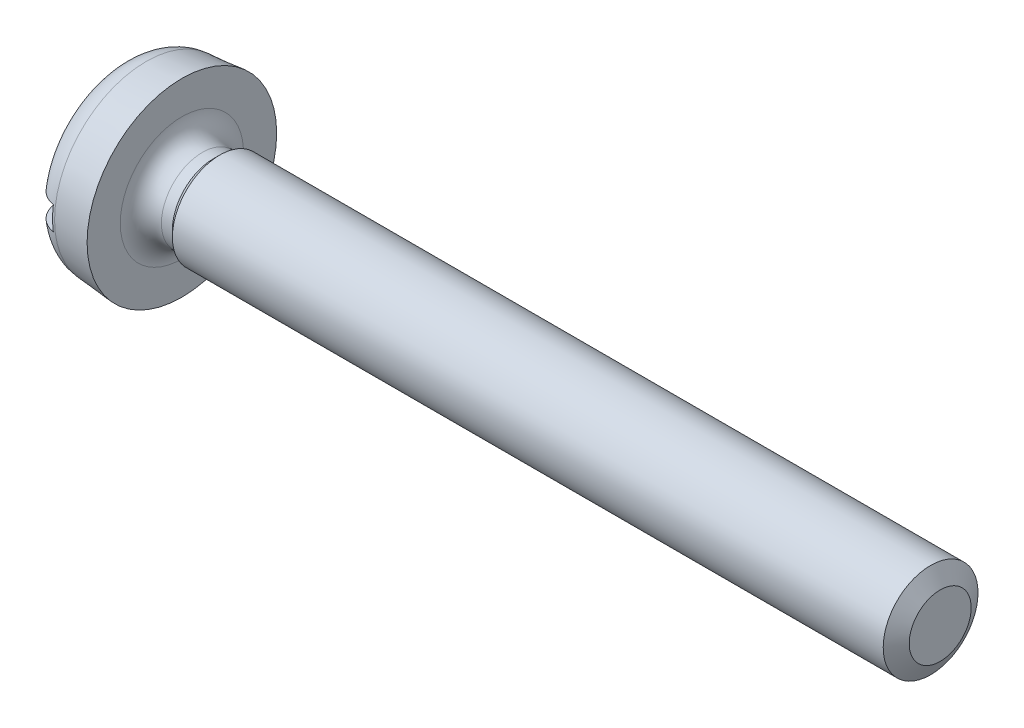
SolidWorks part; units mm, degrees
revolve "基体-旋转" add sketch "草图3" angle 360 about L0
sketch "草图3" plane through (0, 0, 0) normal (0, 0, 1) x (1, 0, 0)
  line L0 (-2.477, 0) -> (6.7868, 0) construction
  line L1 (0, 0) -> (17.3, 0)
  line L2 (17.3, 0) -> (17.3, 1)
  line L3 (17.3, 1) -> (2.1, 1)
  line L4 (1.3, 1.3) -> (1.3, 2)
  line L5 (2.1, 1) -> (1.966, 0.866)
  line L6 (1.966, 0.866) -> (1.734, 0.866)
  line L7 (1.3, 2) -> (0.5477, 1.9342)
  line L9 (0, 1.3365) -> (0, 0)
  arc A0 (1.734, 0.866) -> (1.3, 1.3) centre (1.734, 1.3) cw
  arc A1 (0.5477, 1.9342) -> (0, 1.3365) centre (0.6, 1.3365) ccw
  dimension "D5" = 0.6
  dimension "dk" = 4
  dimension "d" = 2
  dimension "D2" = 5
  dimension "l" = 16
  dimension "D1" = 45
  dimension "D3" = 1.732
  dimension "D4" = 15.2
  dimension "da" = 2.6
  dimension "k" = 1.3
cosmetic thread "装饰螺纹线1" parameters "D1"=15.2, "D2"=1.732
material "4.8级"
ref_plane "前视" through (0, 0, 0) normal (0, 0, 1) x (1, 0, 0)
ref_plane "上视" through (0, 0, 0) normal (0, 1, 0) x (1, 0, 0)
ref_plane "右视" through (0, 0, 0) normal (1, 0, 0) x (0, 0, -1)
sketch "尺寸草图" plane through (0, 0, 0) normal (0, 0, 1) x (1, 0, 0)
  line L0 (0, 0) -> (16, 0)
  line L1 (0, 0) -> (0, 4)
  line L2 (16, 0) -> (16, 2.6)
  point P5 (15.6, 0)
  point P6 (1.3, 0)
  point P7 (0.5, 0)
  point P8 (0.8, 0)
  point P9 (16, 0.1)
  point P10 (15.4, 0)
  point P11 (0, 0.5)
  point P12 (16, 2)
  dimension "dk" = 4
  dimension "d" = 2
  dimension "l" = 16
  dimension "da" = 2.6
  dimension "k" = 1.3
  dimension "P" = 0.4
  dimension "a" = 0.8
  dimension "n" = 0.5
  dimension "r" = 0.1
  dimension "rf" = 0.6
  dimension "t" = 0.5
sketch "草图4" plane through (0, 0, 0) normal (0, 0, 1) x (1, 0, 0)
  line L0 (0, 1.3365) -> (0, -1.3365) construction
  line L1 (0, 0.25) -> (0.5, 0.25)
  line L2 (0, 0.25) -> (0, -0.25)
  line L3 (0, -0.25) -> (0.5, -0.25)
  line L4 (0.5, 0.25) -> (0.5, -0.25)
  point P6 (0, 0)
  dimension "n" = 0.5
  dimension "t" = 0.5
extrude "切除-拉伸1" cut sketch "草图4" against normal mid plane 100
sketch "草图5" plane through (0, 0, 0) normal (0, 0, 1) x (1, 0, 0)
  line L0 (17.0978, 1) -> (17.4978, 1)
  line L1 (17.4978, 1) -> (17.3, 0.6536)
  line L2 (17.3, 0.6536) -> (17.0978, 1)
  line L3 (17.3, 1) -> (2.1, 1) construction
  line L4 (17.3, -1) -> (17.3, 1) construction
  line L5 (6.175, 0) -> (-0.2582, 0) construction
  line L6 (-2.477, 0) -> (6.7868, 0) construction
  dimension "P" = 0.4
  dimension "D1" = 0.3464
  dimension "D2" = 60
revolve "切除-旋转1" cut sketch "草图5" angle 360 about L5
pattern_linear "阵列(线性)1" [suppressed] count 39 spacing 0.4 along (1, 0, 0)
equation "\"l@草图3\" = \"l@尺寸草图\""
equation "\"dk@草图3\"=\"dk@尺寸草图\""
equation "\"da@草图3\" = \"da@尺寸草图\""
equation "\"D3@草图3\" = \"d@尺寸草图\"*0.866"
equation "\"D4@草图3\" = \"l@尺寸草图\"-\"a@尺寸草图\""
equation "\"d@草图3\" = \"d@尺寸草图\""
equation "\"D2@装饰螺纹线1\" = \"d@尺寸草图\"*0.866"
equation "\"D1@装饰螺纹线1\" = \"l@尺寸草图\"-\"a@尺寸草图\""
equation "\"n@草图4\" = \"n@尺寸草图\""
equation "\"t@草图4\" = \"t@尺寸草图\""
equation "\"P@草图5\" = \"P@尺寸草图\""
equation "\"D1@草图5\" = \"P@草图5\"*0.866"
equation "\"D3@阵列(线性)1\" = \"P@尺寸草图\""
equation "\"D1@阵列(线性)1\" = (\"l@尺寸草图\"-\"a@尺寸草图\")/\"P@尺寸草图\"+1"
equation "\"k@草图3\"=\"k@尺寸草图\""
equation "\"D5@草图3\"=\"rf@尺寸草图\""
